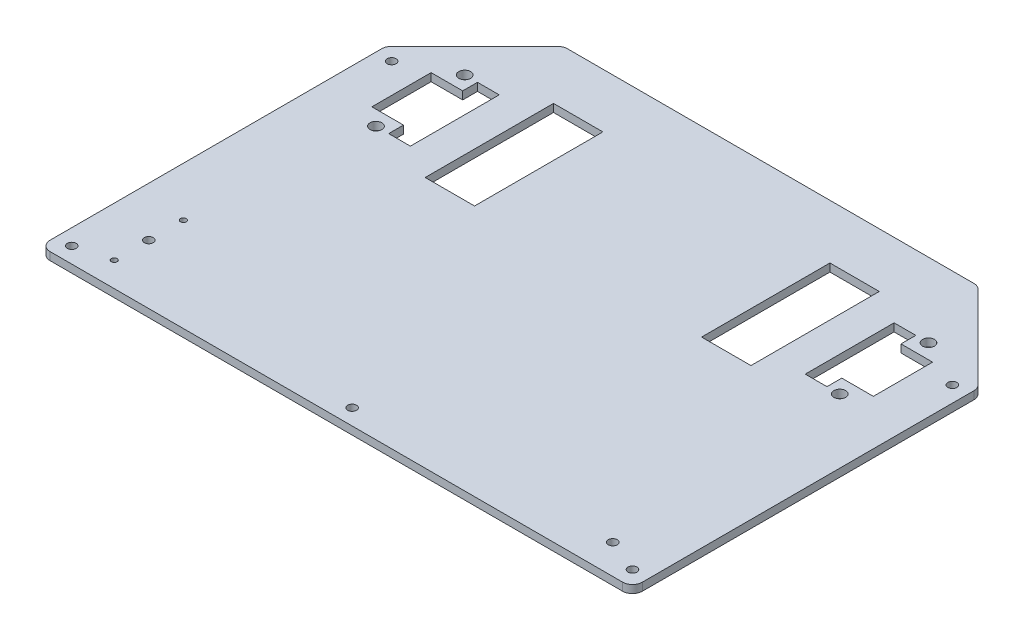
SolidWorks part; units mm, degrees
material "Acier non allié"
ref_plane "Front" through (0, 0, 0) normal (0, 0, 1) x (1, 0, 0)
ref_plane "Top" through (0, 0, 0) normal (0, 1, 0) x (1, 0, 0)
ref_plane "Right" through (0, 0, 0) normal (1, 0, 0) x (0, 0, -1)
sketch "Main scetch" plane through (0, 0, 0) normal (0, 1, 0) x (1, 0, 0)
  line L0 (-150, 0) -> (150, 0)
  line L1 (0, 0) -> (150, 0) construction
  line L2 (0, 0) -> (0, 220) construction
  line L3 (0, 220) -> (150, 220) construction
  line L4 (150, 0) -> (150, 220) construction
  line L5 (150, 0) -> (150, 175)
  line L6 (150, 175) -> (105, 220)
  line L10 (105, 220) -> (-105, 220)
  line L11 (-150, 0) -> (-150, 175)
  line L12 (-150, 175) -> (-105, 220)
  dimension "D1" = 150
  dimension "D2" = 220
  dimension "D3" = 45
  dimension "D4" = 45
extrude "Main extrusion" add sketch "Main scetch" along normal blind 4
fillet "Corner leave" radius 5 6 edges at (-150, 2, 0) (150, 2, -175) (105, 2, -220) (150, 2, 0) (-105, 2, -220) (-150, 2, -175)
sketch "Esquisse2" plane through (0, 4, 0) normal (0, 1, 0) x (1, 0, 0)
  line L0 (-145, 0) -> (145, 0) construction
  line L1 (150, 5) -> (150, 172.9289) construction
  line L2 (148.5355, 176.4645) -> (106.4645, 218.5355) construction
  line L3 (102.9289, 220) -> (-102.9289, 220) construction
  line L4 (-106.4645, 218.5355) -> (-148.5355, 176.4645) construction
  line L5 (-150, 172.9289) -> (-150, 5) construction
  line L6 (-145, 0) -> (145, 0) construction
  line L7 (150, 5) -> (150, 172.9289) construction
  line L8 (148.5355, 176.4645) -> (106.4645, 218.5355) construction
  line L9 (102.9289, 220) -> (-102.9289, 220) construction
  line L10 (-106.4645, 218.5355) -> (-148.5355, 176.4645) construction
  line L11 (-150, 172.9289) -> (-150, 5) construction
  line L12 (0, 0) -> (0, 238.9669) construction
  line L13 (0, 160) -> (165.6987, 160) construction
  line L14 (70, 230.4421) -> (70, 102.0601) construction
  line L15 (57.5, 192.5) -> (82.5, 192.5)
  line L16 (57.5, 192.5) -> (57.5, 127.5)
  line L17 (57.5, 127.5) -> (82.5, 127.5)
  line L18 (82.5, 192.5) -> (82.5, 127.5)
  line L19 (100, 137.5) -> (100, 182.5)
  line L20 (100, 182.5) -> (111, 182.5)
  line L22 (127, 175) -> (127, 145)
  line L23 (100, 137.5) -> (111, 137.5)
  line L35 (111, 182.5) -> (111, 175)
  line L36 (111, 175) -> (127, 175)
  line L37 (111, 137.5) -> (111, 145)
  line L38 (111, 145) -> (127, 145)
  line L39 (-111, 137.5) -> (-111, 145)
  line L40 (-100, 137.5) -> (-111, 137.5)
  line L41 (-100, 137.5) -> (-100, 182.5)
  line L42 (-100, 182.5) -> (-111, 182.5)
  line L43 (-111, 182.5) -> (-111, 175)
  line L44 (-111, 175) -> (-127, 175)
  line L45 (-127, 175) -> (-127, 145)
  line L46 (-111, 145) -> (-127, 145)
  line L47 (-57.5, 127.5) -> (-82.5, 127.5)
  line L48 (-82.5, 192.5) -> (-82.5, 127.5)
  line L49 (-57.5, 192.5) -> (-82.5, 192.5)
  line L50 (-57.5, 192.5) -> (-57.5, 127.5)
  circle A0 centre (117.47, 182.47) radius 3
  circle A1 centre (117.47, 137.53) radius 3
  circle A2 centre (-117.47, 137.53) radius 3
  circle A3 centre (-117.47, 182.47) radius 3
  point P28 (127, 160)
  point P29 (100, 160)
  dimension "D12" = 6
  dimension "D1" = 60
  dimension "D2" = 65
  dimension "D3" = 70
  dimension "D4" = 25
  dimension "D5" = 27
  dimension "D6" = 45
  dimension "D7" = 100
  dimension "D8" = 11
  dimension "D9" = 30
  dimension "D10" = 17.47
  dimension "D11" = 22.47
extrude "Enlèv. mat.-Extru.1" cut sketch "Esquisse2" against normal through all
sketch "Esquisse8" plane through (0, 4, 0) normal (0, 1, 0) x (1, 0, 0)
  line L0 (-150, 172.9289) -> (-150, 5) construction
  line L1 (-145, 0) -> (145, 0) construction
  line L2 (-125, -12.15) -> (-125, 30) construction
  line L3 (150, 5) -> (150, 172.9289) construction
  circle A0 centre (-125, 30) radius 1.5
  circle A1 centre (125, 15) radius 1.5
  circle A2 centre (-125, 12.5) radius 1
  circle A3 centre (-125, 47.5) radius 1
  dimension "D1" = 3
  dimension "D4" = 3
  dimension "D6" = 25
  dimension "D7" = 2
  dimension "D8" = 2
  dimension "D2" = 25
  dimension "D3" = 30
  dimension "D5" = 15
  dimension "D9" = 17.5
  dimension "D10" = 17.5
hole_wizard "Dégagement M41" positions "Esquisse16" profile "Esquisse17" hole size "M4" standard "ISO" end condition through all
sketch "Esquisse16" plane through (0, 4, 0) normal (0, 1, 0) x (1, 0, 0)
  point P0 (-125, 30)
  point P3 (125, 15)
sketch "Esquisse17" plane through (-125, 4, -30) normal (1, 0, 0) x (0, 0, 1)
  line L0 (0, 0) -> (0, 4)
  line L1 (0, 4) -> (2.25, 4)
  line L2 (2.25, 4) -> (2.25, 0)
  line L5 (2.25, 0) -> (0, 0)
  line L11 (0, -6.35) -> (0, 107.95) construction
  dimension "Diamètre du perçage jusqu'au prochain" = 4.5
  dimension "Profondeur du perçage jusqu'au prochain" = 4
sketch "Esquisse18" plane through (0, 4, 0) normal (0, 1, 0) x (1, 0, 0)
  line L0 (-150, 172.9289) -> (-150, 5) construction
  line L1 (-145, 0) -> (145, 0) construction
  line L3 (150, 5) -> (150, 172.9289) construction
  line L4 (0, 0) -> (0, 20.6924) construction
  circle A0 centre (-142, 8) radius 1
  circle A1 centre (-142, 170) radius 1
  circle A4 centre (142, 170) radius 1
  circle A5 centre (142, 8) radius 1
  circle A6 centre (0, 8) radius 1.5
  dimension "D1" = 2
  dimension "D2" = 2
  dimension "D3" = 3
  dimension "D4" = 8
  dimension "D5" = 2
  dimension "D6" = 2
  dimension "D7" = 8
  dimension "D8" = 8
  dimension "D9" = 170
  dimension "D10" = 8
  dimension "D15" = 8
  dimension "D16" = 170
  dimension "D17" = 8
  dimension "D18" = 8
hole_wizard "Dégagement M42" positions "Esquisse19" profile "Esquisse20" hole size "M4" standard "ISO" end condition through all
sketch "Esquisse19" plane through (0, 4, 0) normal (0, 1, 0) x (1, 0, 0)
  point P0 (-142, 8)
  point P3 (0, 8)
  point P6 (142, 8)
  point P9 (142, 170)
  point P12 (-142, 170)
sketch "Esquisse20" plane through (-142, 4, -8) normal (1, 0, 0) x (0, 0, 1)
  line L0 (0, 0) -> (0, 4)
  line L1 (0, 4) -> (2.25, 4)
  line L2 (2.25, 4) -> (2.25, 0)
  line L5 (2.25, 0) -> (0, 0)
  line L11 (0, -6.35) -> (0, 107.95) construction
  dimension "Diamètre du perçage jusqu'au prochain" = 4.5
  dimension "Profondeur du perçage jusqu'au prochain" = 4
hole_wizard "Dégagement M2.51" positions "Esquisse21" profile "Esquisse22" hole size "M2.5" standard "ISO" end condition through all
sketch "Esquisse21" plane through (0, 4, 0) normal (0, 1, 0) x (1, 0, 0)
  point P0 (-125, 47.5)
  point P3 (-125, 12.5)
sketch "Esquisse22" plane through (-125, 4, -47.5) normal (1, 0, 0) x (0, 0, 1)
  line L0 (0, 0) -> (0, 4)
  line L1 (0, 4) -> (1.45, 4)
  line L2 (1.45, 4) -> (1.45, 0)
  line L5 (1.45, 0) -> (0, 0)
  line L11 (0, -6.35) -> (0, 107.95) construction
  dimension "Diamètre du perçage jusqu'au prochain" = 2.9
  dimension "Profondeur du perçage jusqu'au prochain" = 4
equation "\"WIDTH\"= 300mm'Total width of the robot"
equation "\"LENGTH\"= 220mm'Total length of the robot"
equation "\"D1@Main scetch\" = \"WIDTH\" / 2"
equation "\"D2@Main scetch\" = \"LENGTH\""
equation "\"CUT_DEPTH\"= 45mm'Depth of the cut on the edges of the plate"
equation "\"D3@Main scetch\" = \"CUT_DEPTH\""
equation "\"D4@Main scetch\" = \"CUT_DEPTH\""
equation "\"Plate_th\"= 3mm'Thickness of the plate"
equation "\"D1\"= \"Plate_th\""
